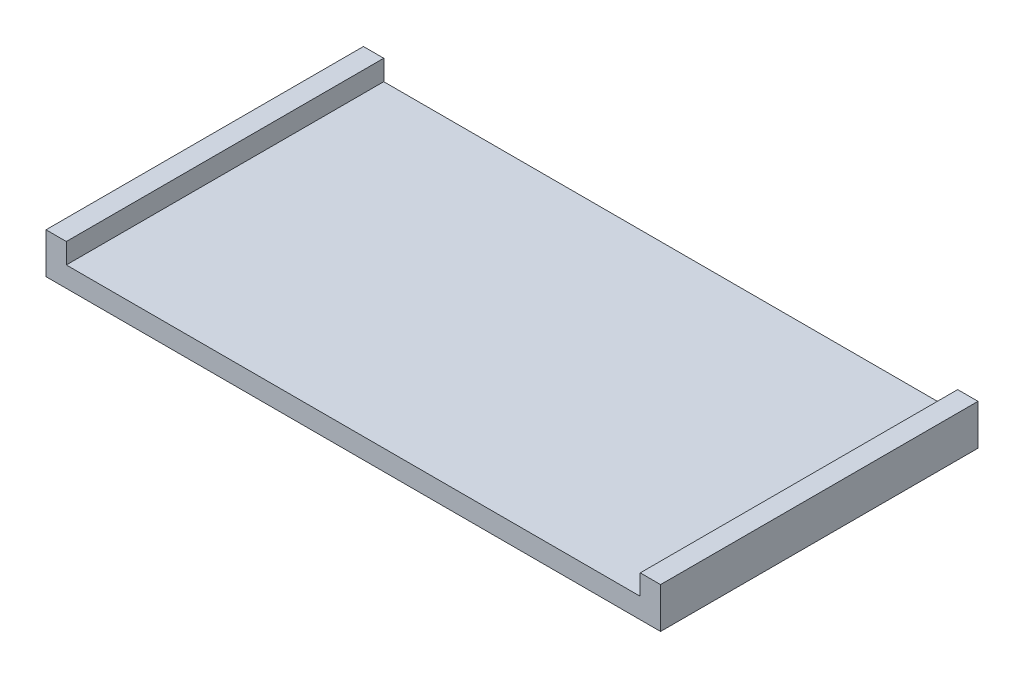
SolidWorks part; units mm, degrees
ref_plane "Front Plane" through (0, 0, 0) normal (0, 0, 1) x (1, 0, 0)
ref_plane "Top Plane" through (0, 0, 0) normal (0, 1, 0) x (1, 0, 0)
ref_plane "Right Plane" through (0, 0, 0) normal (1, 0, 0) x (0, 0, -1)
sketch "Sketch1" plane through (0, 0, 0) normal (0, 1, 0) x (1, 0, 0)
  line L0 (0, 0) -> (24.2, 0)
  line L1 (0, 0) -> (-24.2, 0)
  line L2 (-24.2, 0) -> (-24.2, 25)
  line L3 (-24.2, 25) -> (24.2, 25)
  line L4 (24.2, 25) -> (24.2, 0)
extrude "Boss-Extrude1" add sketch "Sketch1" along normal blind 1.6
sketch "Sketch2" plane through (0, 1.6, 0) normal (0, 1, 0) x (1, 0, 0)
  line L0 (-24.2, 25) -> (-24.2, 0) construction
  line L1 (24.2, 0) -> (24.2, 25) construction
  line L2 (-24.2, 25) -> (-24.2, 0)
  line L3 (24.2, 0) -> (24.2, 25)
  line L4 (-22.6, 25) -> (-22.6, 0)
  line L5 (22.6, 0) -> (22.6, 25)
  line L6 (-24.2, 25) -> (-22.6, 25)
  line L7 (24.2, 0) -> (22.6, 0)
  line L8 (22.6, 25) -> (24.2, 25)
  line L9 (-22.6, 0) -> (-24.2, 0)
  dimension "D1" = 1.6
extrude "Boss-Extrude2" add sketch "Sketch2" along normal blind 1.6
